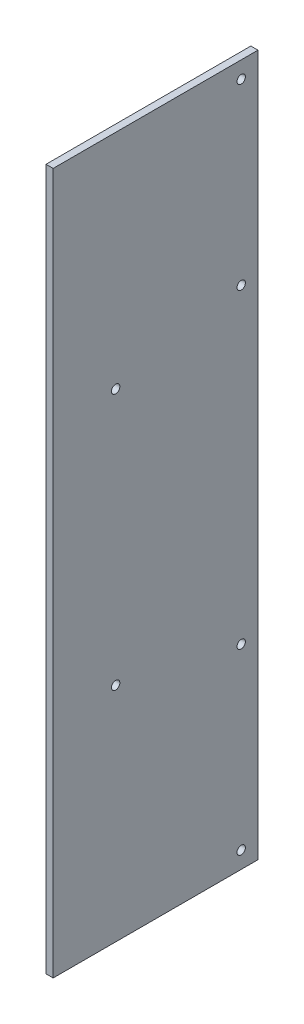
SolidWorks part; units mm, degrees
ref_plane "Front Plane" through (0, 0, 0) normal (0, 0, 1) x (1, 0, 0)
ref_plane "Top Plane" through (0, 0, 0) normal (0, 1, 0) x (1, 0, 0)
ref_plane "Right Plane" through (0, 0, 0) normal (1, 0, 0) x (0, 0, -1)
sketch "Sketch1" plane through (0, 0, 0) normal (1, 0, 0) x (0, 0, -1)
  line L0 (0, 0) -> (0, -139.192)
  line L1 (0, 0) -> (139.192, 0)
  line L2 (0, 0) -> (113.8047, -71.9099)
  line L3 (0, -129.54) -> (91.3565, -129.54)
  line L5 (129.54, 0) -> (139.192, 0)
  line L6 (0, 0) -> (154.94, 0)
  line L7 (0, 0) -> (0, -160.3502)
  line L8 (0, -160.3502) -> (154.94, -160.3502)
  line L9 (154.94, 0) -> (154.94, -160.3502)
  line L10 (0, -129.54) -> (-8.3464, -129.54)
  line L11 (0, -129.54) -> (0, -160.3502)
  line L12 (0, -160.3502) -> (-8.3464, -160.3502)
  line L13 (-8.3464, -129.54) -> (-8.3464, -160.3502)
  line L14 (0, -160.3502) -> (-49.6214, -160.3502)
  line L15 (0, -160.3502) -> (0, -134.9502)
  line L16 (0, -134.9502) -> (-49.6214, -134.9502)
  line L17 (-49.6214, -160.3502) -> (-49.6214, -134.9502)
  line L18 (-8.3464, -129.54) -> (0, -129.54)
  line L19 (-8.3464, -129.54) -> (-8.3464, 0)
  line L20 (-8.3464, 0) -> (0, 0)
  line L21 (0, -129.54) -> (0, 0)
  circle A0 centre (0, 0) radius 129.54
  circle A1 centre (0, 0) radius 139.192
  circle A2 centre (-36.9214, -147.6502) radius 3.175
  circle A3 centre (142.24, -12.7) radius 3.175
  circle A4 centre (142.24, -147.6502) radius 3.175
  dimension "D1" = 9.652
  dimension "D4" = 134.62
  dimension "D5" = 30.8102
  dimension "D3" = 259.08
  dimension "D9" = 12.7
  dimension "D11" = 12.7
  dimension "D13" = 12.7
  dimension "D2" = 25.4
  dimension "D6" = 8.3464
  dimension "D7" = 49.6214
  dimension "D8" = 25.4
  dimension "D10" = 12.7
  dimension "D12" = 12.7
  dimension "D14" = 12.7
  dimension "D15" = 8.3464
  dimension "D16" = 129.54
extrude "Boss-Extrude3" add sketch "Sketch1" along normal blind 5.4102
sketch "Sketch5" plane through (5.4102, 0, 0) normal (1, 0, 0) x (0, 0, -1)
  line L0 (-8.3464, -160.3502) -> (154.94, -160.3502)
  line L1 (-8.3464, 0) -> (154.94, 0)
  line L2 (-8.3464, 0) -> (-8.3464, -530.3368)
  line L3 (-8.3464, -530.3368) -> (154.94, -530.3368)
  line L4 (154.94, 0) -> (154.94, -530.3368)
  line L5 (-8.3464, -160.3502) -> (154.94, -160.3502) construction
  line L6 (154.94, 0) -> (154.94, -160.3502) construction
  circle A0 centre (47.2796, -168.148) radius 3.175
  circle A1 centre (47.2796, -362.1888) radius 3.175
  line M4 (-8.3464, -160.3502) -> (154.94, -160.3502)
  dimension "D1" = 55.626
  dimension "D3" = 194.0408
  dimension "D5" = 0
  dimension "D2" = 168.148
  dimension "D4" = 0
  dimension "D6" = 168.148
  dimension "D7" = 0
extrude "Boss-Extrude7" add sketch "Sketch5" against normal up to surface (5.4102 mm away) contours L4 L2 L3 A1 A0 M4 up to face at (0, -80.1751, -73.2968)
sketch "Sketch6" plane through (0, 0, 0) normal (-1, 0, 0) x (0, 0, 1)
  line L0 (-154.94, -530.3368) -> (8.3464, -530.3368) construction
  line L1 (8.3464, 0) -> (0, 0)
  line L2 (8.3464, 0) -> (8.3464, -530.3368)
  line L3 (8.3464, -530.3368) -> (0, -530.3368)
  line L4 (0, 0) -> (0, -530.3368)
  dimension "D1" = 8.3464
extrude "Cut-Extrude1" cut sketch "Sketch6" against normal blind 5.4102
sketch "Sketch7" plane through (0, 0, 0) normal (-1, 0, 0) x (0, 0, 1)
  line L0 (-154.94, 0) -> (-154.94, -530.3368) construction
  line L1 (-154.94, -530.3368) -> (0, -530.3368) construction
  circle A0 centre (-142.24, -517.6368) radius 3.175
  circle A1 centre (-142.24, -382.7628) radius 3.175
  dimension "D1" = 12.7
  dimension "D2" = 12.7
  dimension "D3" = 12.7
  dimension "D4" = 134.874
extrude "Cut-Extrude2" cut sketch "Sketch7" against normal blind 5.4102
